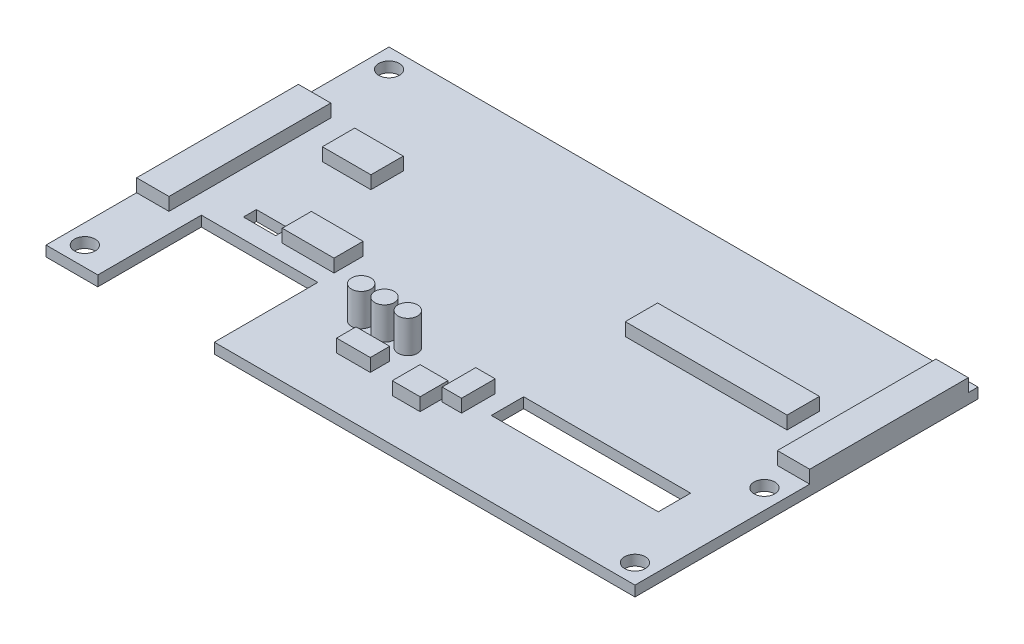
SolidWorks part; units mm, degrees
ref_plane "前视基准面" through (0, 0, 0) normal (0, 0, 1) x (1, 0, 0)
ref_plane "上视基准面" through (0, 0, 0) normal (0, 1, 0) x (1, 0, 0)
ref_plane "右视基准面" through (0, 0, 0) normal (1, 0, 0) x (0, 0, -1)
sketch "草图2" plane through (0, 0, 0) normal (0, 1, 0) x (1, 0, 0)
  line L0 (0, 0) -> (0, -53)
  line L1 (0, 0) -> (91, 0) construction
  line L2 (0, 0) -> (0, -53) construction
  line L3 (0, -53) -> (91, -53) construction
  line L4 (91, 0) -> (91, -53) construction
  line L5 (8, -53) -> (26, -53) construction
  line L6 (8, -53) -> (8, -37) construction
  line L7 (8, -37) -> (26, -37) construction
  line L8 (26, -53) -> (26, -37) construction
  line L9 (0, -53) -> (8, -53)
  line L10 (8, -53) -> (8, -37)
  line L11 (8, -37) -> (26, -37)
  line L12 (26, -37) -> (26, -53)
  line L13 (26, -53) -> (91, -53)
  line L14 (91, -53) -> (91, 0)
  line L15 (91, 0) -> (0, 0)
  line L17 (11.5, -34) -> (16.5, -34)
  line L18 (11.5, -34) -> (11.5, -32)
  line L19 (11.5, -32) -> (16.5, -32)
  line L20 (16.5, -34) -> (16.5, -32)
  line L21 (83, -41.4) -> (57.2, -41.4)
  line L22 (83, -41.4) -> (83, -36.4)
  line L23 (83, -36.4) -> (57.2, -36.4)
  line L24 (57.2, -41.4) -> (57.2, -36.4)
  circle A0 centre (3, -50) radius 1.6
  circle A1 centre (3, -3) radius 1.6
  circle A2 centre (88, -30) radius 1.6
  circle A3 centre (88, -50) radius 1.6
  dimension "D14" = 3.2
  dimension "D15" = 3.2
  dimension "D16" = 3.2
  dimension "D17" = 3.2
  dimension "D1" = 91
  dimension "D2" = 53
  dimension "D3" = 8
  dimension "D4" = 18
  dimension "D5" = 16
  dimension "D6" = 11.5
  dimension "D7" = 19
  dimension "D8" = 5
  dimension "D9" = 2
  dimension "D10" = 8
  dimension "D11" = 11.6
  dimension "D12" = 25.8
  dimension "D13" = 5
  dimension "D18" = 3
  dimension "D19" = 3
  dimension "D20" = 3
  dimension "D21" = 3
  dimension "D22" = 3
  dimension "D23" = 3
  dimension "D24" = 3
  dimension "D25" = 23
extrude "凸台-拉伸1" add sketch "草图2" along normal blind 1.6
sketch "草图3" plane through (0, 1.6, 0) normal (0, 1, 0) x (1, 0, 0)
  line L0 (0, 0) -> (0, -53) construction
  line L1 (5, -14) -> (0, -14)
  line L2 (5, -14) -> (5, -39)
  line L3 (5, -39) -> (0, -39)
  line L4 (0, -14) -> (0, -39)
  line L5 (91, 0) -> (0, 0) construction
  line L6 (10.2, -15.5) -> (17.7, -15.5)
  line L7 (10.2, -15.5) -> (10.2, -20.5)
  line L8 (10.2, -20.5) -> (17.7, -20.5)
  line L9 (17.7, -15.5) -> (17.7, -20.5)
  line L10 (18, -34.5) -> (26, -34.5)
  line L11 (18, -34.5) -> (18, -30)
  line L12 (18, -30) -> (26, -30)
  line L13 (26, -34.5) -> (26, -30)
  line L14 (57, -20.5) -> (82, -20.5)
  line L15 (57, -20.5) -> (57, -15.5)
  line L16 (57, -15.5) -> (82, -15.5)
  line L17 (82, -20.5) -> (82, -15.5)
  line L22 (91, -53) -> (91, 0) construction
  line L24 (91, -1.5) -> (86, -1.5)
  line L25 (91, -1.5) -> (91, -26)
  line L26 (91, -26) -> (86, -26)
  line L27 (86, -1.5) -> (86, -26)
  dimension "D1" = 14
  dimension "D2" = 25
  dimension "D3" = 5
  dimension "D4" = 15.5
  dimension "D5" = 10.2
  dimension "D6" = 5
  dimension "D7" = 7.5
  dimension "D8" = 30
  dimension "D9" = 18
  dimension "D10" = 8
  dimension "D11" = 4.5
  dimension "D12" = 15.5
  dimension "D13" = 9
  dimension "D14" = 25
  dimension "D15" = 5
  dimension "D16" = 1.5
  dimension "D17" = 24.5
  dimension "D18" = 5
extrude "凸台-拉伸2" add sketch "草图3" along normal blind 2
sketch "草图4" plane through (0, 1.6, 0) normal (0, 1, 0) x (1, 0, 0)
  line L0 (0, -38.8) -> (51.129, -38.8) construction
  line L1 (0, -39) -> (0, -53) construction
  line L2 (0, -53) -> (8, -53) construction
  circle A0 centre (34.5, -38.8) radius 1.5
  circle A1 centre (38.1, -38.8) radius 1.5
  circle A2 centre (41.7, -38.8) radius 1.5
  dimension "D1" = 3
  dimension "D2" = 3
  dimension "D7" = 3
  dimension "D3" = 14.2
  dimension "D4" = 34.5
  dimension "D5" = 3.6
  dimension "D6" = 3.6
extrude "凸台-拉伸3" add sketch "草图4" along normal blind 5
sketch "草图5" plane through (0, 1.6, 0) normal (0, 1, 0) x (1, 0, 0)
  line L0 (26, -53) -> (91, -53) construction
  line L1 (36.9, -42) -> (42.1, -42)
  line L2 (36.9, -42) -> (36.9, -45)
  line L3 (36.9, -45) -> (42.1, -45)
  line L4 (42.1, -42) -> (42.1, -45)
  line L5 (46.9, -42.1) -> (51.2, -42.1)
  line L6 (46.9, -42.1) -> (46.9, -46.4)
  line L7 (46.9, -46.4) -> (51.2, -46.4)
  line L8 (51.2, -42.1) -> (51.2, -46.4)
  line L9 (51.6, -38.2) -> (54.6, -38.2)
  line L10 (51.6, -38.2) -> (51.6, -43.4)
  line L11 (51.6, -43.4) -> (54.6, -43.4)
  line L12 (54.6, -38.2) -> (54.6, -43.4)
  line L13 (0, -39) -> (0, -53) construction
  dimension "D1" = 5.2
  dimension "D2" = 3
  dimension "D3" = 5.2
  dimension "D4" = 3
  dimension "D5" = 8
  dimension "D6" = 36.9
  dimension "D7" = 46.9
  dimension "D8" = 6.6
  dimension "D9" = 4.3
  dimension "D10" = 4.3
  dimension "D11" = 9.6
  dimension "D12" = 51.6
extrude "凸台-拉伸4" add sketch "草图5" along normal blind 2
